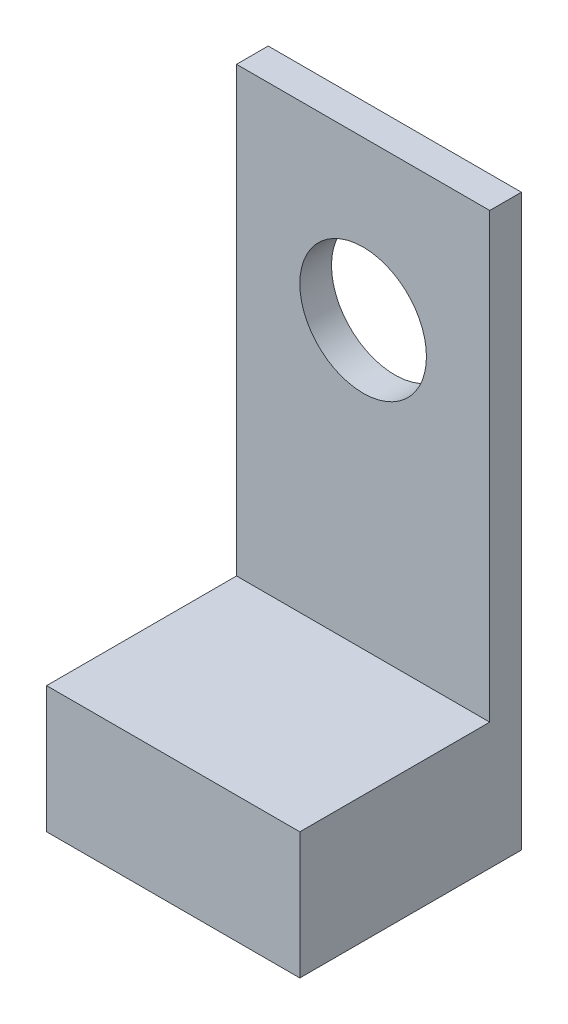
SolidWorks part; units mm, degrees
ref_plane "Front Plane" through (0, 0, 0) normal (0, 0, 1) x (1, 0, 0)
ref_plane "Top Plane" through (0, 0, 0) normal (0, 1, 0) x (1, 0, 0)
ref_plane "Right Plane" through (0, 0, 0) normal (1, 0, 0) x (0, 0, -1)
sketch "Sketch1" plane through (0, 0, 0) normal (0, 0, 1) x (1, 0, 0)
  line L1 (-20.1073, 59.6031) -> (19.8927, 59.6031)
  line L2 (-20.1073, 59.6031) -> (-20.1073, -30.3969)
  line L3 (-20.1073, -30.3969) -> (19.8927, -30.3969)
  line L4 (19.8927, 59.6031) -> (19.8927, -30.3969)
  line L5 (-20.1073, 59.6031) -> (19.8927, -30.3969) construction
  line L6 (-20.1073, -30.3969) -> (19.8927, 59.6031) construction
  point P0 (-0.1073, 14.6031)
  dimension "D1" = 40
  dimension "D2" = 90
extrude "Boss-Extrude1" add sketch "Sketch1" along normal blind 5
sketch "Sketch2" plane through (0, 0, 5) normal (0, 0, 1) x (1, 0, 0)
  line L0 (-20.1073, 59.6031) -> (-20.1073, -30.3969) construction
  line L1 (-20.1073, -30.3969) -> (19.8927, -30.3969)
  line L2 (-20.1073, -30.3969) -> (-20.1073, -10.3969)
  line L3 (-20.1073, -10.3969) -> (19.8927, -10.3969)
  line L4 (19.8927, -30.3969) -> (19.8927, -10.3969)
  line L5 (-20.1073, -30.3969) -> (19.8927, -30.3969) construction
  line L6 (19.8927, -30.3969) -> (19.8927, 59.6031) construction
  dimension "D1" = 20
extrude "Boss-Extrude2" add sketch "Sketch2" along normal blind 30
sketch "Sketch3" plane through (0, 0, 0) normal (0, 0, -1) x (-1, 0, 0)
  line L0 (-19.8927, 59.6031) -> (20.1073, 59.6031) construction
  line L1 (20.1073, 59.6031) -> (20.1073, -30.3969) construction
  circle A0 centre (0.1073, 34.6031) radius 10
  dimension "D1" = 25
  dimension "20" = 20
  dimension "D2" = 20
extrude "Cut-Extrude1" cut sketch "Sketch3" against normal blind 30
